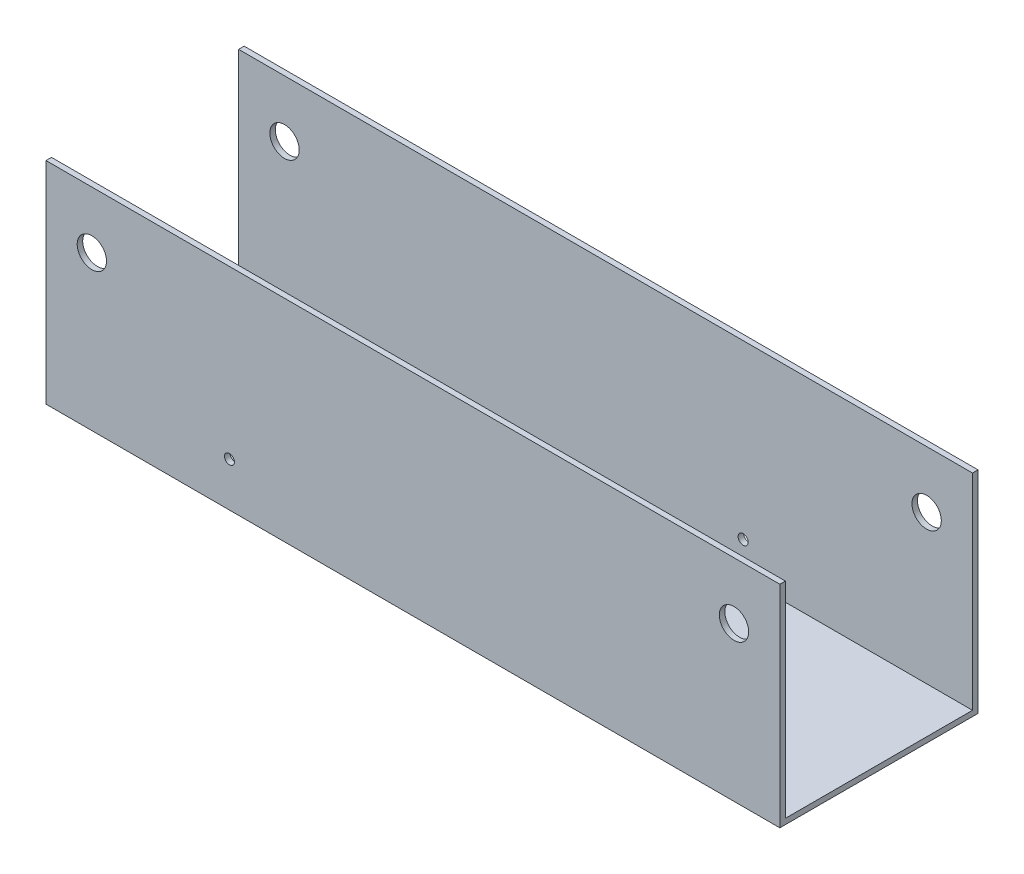
SolidWorks part; units mm, degrees
ref_plane "Front Plane" through (0, 0, 0) normal (0, 0, 1) x (1, 0, 0)
ref_plane "Top Plane" through (0, 0, 0) normal (0, 1, 0) x (1, 0, 0)
ref_plane "Right Plane" through (0, 0, 0) normal (1, 0, 0) x (0, 0, -1)
sketch "Sketch1" plane through (0, 0, 0) normal (0, 1, 0) x (1, 0, 0)
  line L1 (-133.8195, 144.485) -> (266.1805, 144.485)
  line L2 (-133.8195, 144.485) -> (-133.8195, 36.485)
  line L3 (-133.8195, 36.485) -> (266.1805, 36.485)
  line L4 (266.1805, 144.485) -> (266.1805, 36.485)
  line L5 (-133.8195, 141.485) -> (266.1805, 141.485)
  line L6 (-133.8195, 141.485) -> (-133.8195, 39.485)
  line L7 (-133.8195, 39.485) -> (266.1805, 39.485)
  line L8 (266.1805, 141.485) -> (266.1805, 39.485)
  dimension "D1" = 400
  dimension "D2" = 108
  dimension "D3" = 3
  dimension "D4" = 3
extrude "Boss-Extrude1" add sketch "Sketch1" along normal blind 65 contours L3 L4 L1 L2
sketch "Sketch3" plane through (0, 0, 0) normal (0, -1, 0) x (1, 0, 0)
  line L0 (-133.8195, -144.485) -> (-133.8195, -36.485) construction
  line L1 (-133.8195, -39.485) -> (266.1805, -39.485)
  line L2 (-133.8195, -39.485) -> (-133.8195, -141.485)
  line L3 (-133.8195, -141.485) -> (266.1805, -141.485)
  line L4 (266.1805, -39.485) -> (266.1805, -141.485)
  line L5 (266.1805, -144.485) -> (266.1805, -36.485) construction
  line L6 (-133.8195, -36.485) -> (266.1805, -36.485) construction
  line L7 (-133.8195, -144.485) -> (266.1805, -144.485) construction
  dimension "D1" = 3
  dimension "D2" = 3
extrude "Cut-Extrude1" cut sketch "Sketch3" against normal blind 158
sketch "Sketch4" plane through (0, 0, -36.485) normal (0, 0, 1) x (1, 0, 0)
  line L0 (-133.8195, 65) -> (266.1805, 65) construction
  line L1 (-133.8195, 65) -> (-133.8195, 0) construction
  line L2 (266.1805, 65) -> (266.1805, 0) construction
  circle A0 centre (-108.8195, 34) radius 8
  circle A1 centre (241.1805, 34) radius 8
  dimension "D1" = 16
  dimension "D2" = 31
  dimension "D3" = 25
  dimension "D4" = 25
  dimension "D5" = 16
  dimension "D6" = 31
extrude "Cut-Extrude2" cut sketch "Sketch4" against normal blind 158
sketch "Sketch6" plane through (0, 0, 0) normal (0, -1, 0) x (1, 0, 0)
  line L1 (-133.8195, -36.485) -> (266.1805, -36.485)
  line L2 (-133.8195, -36.485) -> (-133.8195, -39.485)
  line L3 (-133.8195, -39.485) -> (266.1805, -39.485)
  line L4 (266.1805, -36.485) -> (266.1805, -39.485)
  line L5 (-133.8195, -141.485) -> (266.1805, -141.485)
  line L6 (-133.8195, -141.485) -> (-133.8195, -144.485)
  line L7 (-133.8195, -144.485) -> (266.1805, -144.485)
  line L8 (266.1805, -141.485) -> (266.1805, -144.485)
extrude "Boss-Extrude3" add sketch "Sketch6" along normal blind 50
sketch "Sketch7" plane through (0, 0, -39.485) normal (0, 0, -1) x (-1, 0, 0)
  line L0 (-266.1805, 65) -> (-266.1805, -50) construction
  line L1 (-266.1805, -47) -> (133.8195, -47)
  line L2 (-266.1805, -47) -> (-266.1805, -50)
  line L3 (-266.1805, -50) -> (133.8195, -50)
  line L4 (133.8195, -47) -> (133.8195, -50)
  line L5 (133.8195, 65) -> (133.8195, -50) construction
  line L6 (133.8195, -50) -> (-266.1805, -50) construction
  dimension "D1" = 3
extrude "Boss-Extrude4" add sketch "Sketch7" along normal blind 102
sketch "Sketch11" plane through (0, 0, -36.485) normal (0, 0, 1) x (1, 0, 0)
  line L0 (266.1805, -50) -> (-133.8195, -50) construction
  line L1 (-133.8195, 65) -> (-133.8195, -50) construction
  circle A0 centre (-33.8195, -25.95) radius 2.7
  dimension "D1" = 5.4
  dimension "D2" = 24.05
  dimension "D3" = 100
extrude "Cut-Extrude4" cut sketch "Sketch11" against normal blind 75
sketch "Sketch10" plane through (0, 0, -144.485) normal (0, 0, -1) x (-1, 0, 0)
  line L0 (133.8195, -50) -> (-266.1805, -50) construction
  line L1 (-266.1805, 65) -> (-266.1805, -50) construction
  circle A0 centre (-141.1805, -28.85) radius 2.75
  dimension "D1" = 5.5
  dimension "D2" = 21.15
  dimension "D3" = 125
extrude "Cut-Extrude3" cut sketch "Sketch10" against normal blind 75
